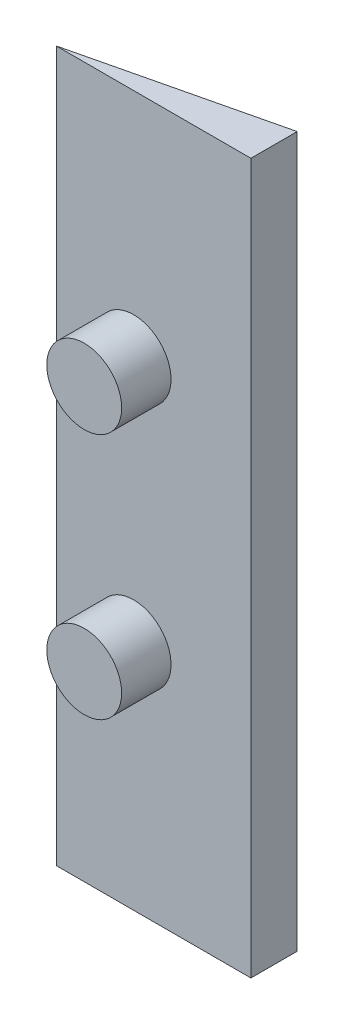
SolidWorks part; units mm, degrees
ref_plane "Front Plane" through (0, 0, 0) normal (0, 0, 1) x (1, 0, 0)
ref_plane "Top Plane" through (0, 0, 0) normal (0, 1, 0) x (1, 0, 0)
ref_plane "Right Plane" through (0, 0, 0) normal (1, 0, 0) x (0, 0, -1)
sketch "Sketch1" plane through (0, 0, 0) normal (0, 1, 0) x (1, 0, 0)
  line L0 (-6.3, 0) -> (6.3, 0)
  line L5 (-6.3, 0) -> (6.3, 3)
  line L6 (6.3, 3) -> (6.3, 0)
  point P3 (0, 0)
  dimension "D1" = 12.6
  dimension "D2" = 3
extrude "Boss-Extrude1" add sketch "Sketch1" along normal mid plane 46
sketch "Sketch2" plane through (0, 0, 0) normal (0, 0, 1) x (1, 0, 0)
  line L0 (-1.3, 8) -> (-1.3, 0) construction
  line L1 (-1.3, 0) -> (-1.3, -8) construction
  line L2 (-6.3, 23) -> (-6.3, -23) construction
  circle A0 centre (-1.3, 8) radius 2.425
  circle A1 centre (-1.3, -8) radius 2.425
  point P4 (0, 0)
  point P9 (0, 0)
  dimension "D2" = 4.85
  dimension "D3" = 16
  dimension "D4" = 5
extrude "Boss-Extrude2" add sketch "Sketch2" along normal blind 3.2
